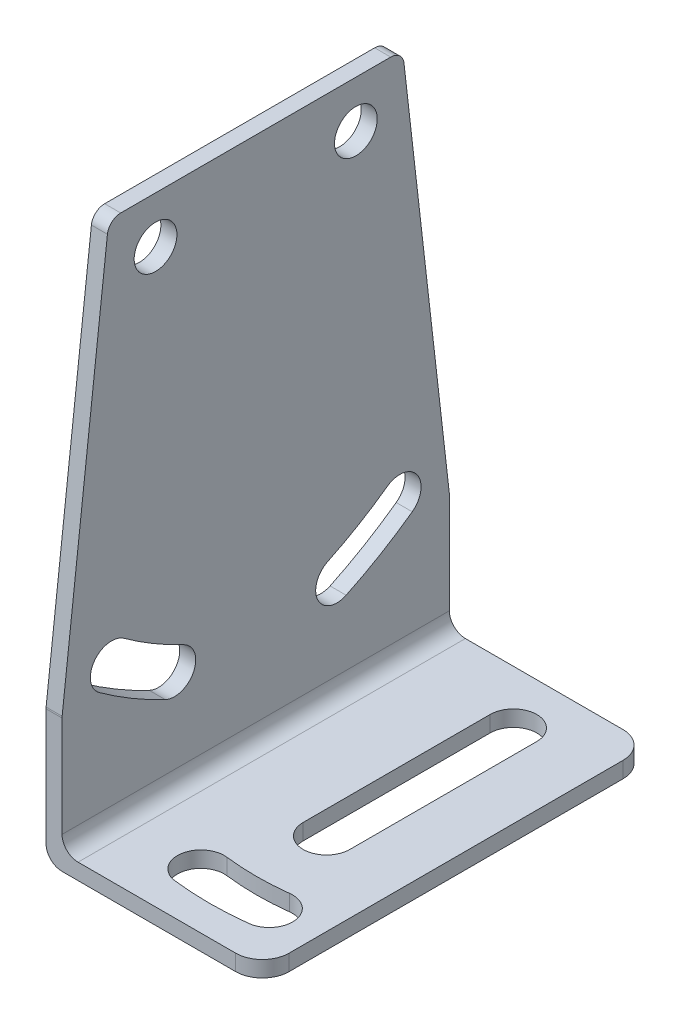
SolidWorks part; units mm, degrees
material "Cast Stainless Steel"
ref_plane "Front Plane" through (0, 0, 0) normal (0, 0, 1) x (1, 0, 0)
ref_plane "Top Plane" through (0, 0, 0) normal (0, 1, 0) x (1, 0, 0)
ref_plane "Right Plane" through (0, 0, 0) normal (1, 0, 0) x (0, 0, -1)
sketch "Sketch1" plane through (0, 0, 0) normal (1, 0, 0) x (0, 0, -1)
  line L0 (0, 0) -> (0, -40.5) construction
  line L1 (-7.5, 0) -> (7.5, 0)
  line L2 (-7.5, -3.5) -> (8.5, -30.5) construction
  line L3 (-7.5, -3.5) -> (10.7896, -28.9989) construction
  line L4 (-7.5, -3.5) -> (6.0839, -31.7875) construction
  line L5 (-14.5, -40.5) -> (14.5, -40.5)
  line L6 (7.5, 0) -> (10.1082, 0)
  line L7 (11.1017, -0.886) -> (14.4935, -30.4432)
  line L8 (14.5, -30.5572) -> (14.5, -40.5)
  line L9 (-7.5, 0) -> (-10.1082, 0)
  line L10 (-11.1017, -0.886) -> (-14.4935, -30.4421)
  line L11 (-14.5, -30.5561) -> (-14.5, -40.5)
  circle A0 centre (-7.5, -3.5) radius 1.6
  arc A2 (9.857, -27.6988) -> (9.736, -27.7948) centre (10.7896, -28.9989) ccw
  arc A3 (5.5335, -30.2851) -> (5.3913, -30.3452) centre (6.0839, -31.7875) ccw
  arc A4 (10.7896, -28.9989) -> (6.0839, -31.7875) centre (-7.0515, -4.2569) cw construction
  arc A5 (6.7696, -33.2248) -> (11.721, -30.2907) centre (-7.0515, -4.2569) ccw
  arc A6 (5.3981, -30.3502) -> (9.8581, -27.7072) centre (-7.0515, -4.2569) ccw
  arc A7 (5.3981, -30.3502) -> (6.7696, -33.2248) centre (6.0839, -31.7875) ccw
  arc A8 (11.721, -30.2907) -> (9.8581, -27.7072) centre (10.7896, -28.9989) ccw
  arc A9 (-10.7896, -28.9989) -> (-6.0839, -31.7875) centre (7.0515, -4.2569) ccw construction
  arc A10 (-6.7696, -33.2248) -> (-11.721, -30.2907) centre (7.0515, -4.2569) cw
  arc A11 (-5.3981, -30.3502) -> (-9.8581, -27.7072) centre (7.0515, -4.2569) cw
  arc A12 (-5.3981, -30.3502) -> (-6.7696, -33.2248) centre (-6.0839, -31.7875) cw
  arc A13 (-11.721, -30.2907) -> (-9.8581, -27.7072) centre (-10.7896, -28.9989) cw
  circle A14 centre (7.5, -3.5) radius 1.6
  arc A15 (-14.4935, -30.4421) -> (-14.5, -30.5561) centre (-13.5, -30.5561) ccw
  arc A16 (14.4935, -30.4432) -> (14.5, -30.5572) centre (13.5, -30.5572) cw
  arc A17 (10.1082, 0) -> (11.1017, -0.886) centre (10.1082, -1) cw
  arc A18 (-10.1082, 0) -> (-11.1017, -0.886) centre (-10.1082, -1) ccw
  point P15 (8.4994, -30.4989)
  point P23 (7.5, -3.5)
  point P24 (-8.4994, -30.4989)
  point P39 (-14.5, -30.4989)
  point P42 (14.5, -30.5)
  point P45 (11, 0)
  point P48 (-11, 0)
  dimension "D3" = 27
  dimension "D16" = 3.2
  dimension "D17" = 3.2
  dimension "D18" = 3.5
  dimension "D21" = 1
  dimension "D1" = 15
  dimension "D2" = 7.5
  dimension "D4" = 29
  dimension "D5" = 3.5
  dimension "D6" = 7.5
  dimension "D7" = 14.5
  dimension "D8" = 40.5
  dimension "D9" = 16
  dimension "D10" = 3.5
  dimension "D11" = 31.3847
  dimension "D12" = 31.38
  dimension "D13" = 31.38
  dimension "D14" = 10
  dimension "D15" = 5
  dimension "D19" = 10
  dimension "D20" = 10.0011
extrude "Boss-Extrude1" add sketch "Sketch1" along normal blind 1.2 contours A15 L10 A18 L9 L1 L6 A17 L7 A16 L8 L5 L11 | A6 A8 A5 A7 | A10 A13 A11 A12 | A0 | A14
sketch "Sketch2" plane through (1.2, 0, 0) normal (1, 0, 0) x (0, 0, -1)
  line L1 (-14.5, -40.5) -> (14.5, -40.5)
  line L2 (-14.5, -40.5) -> (-14.5, -39.3)
  line L3 (-14.5, -39.3) -> (14.5, -39.3)
  line L4 (14.5, -40.5) -> (14.5, -39.3)
  line L5 (14.5, -30.5572) -> (14.5, -40.5) construction
  dimension "D1" = 1.2
  dimension "D2" = 29
extrude "Boss-Extrude2" add sketch "Sketch2" along normal blind 15
sketch "Sketch3" plane through (0, -39.3, 0) normal (0, 1, 0) x (1, 0, 0)
  line L0 (10, 17.234) -> (10, -18.6155) construction
  line L1 (0, 11.1017) -> (0, 14.4935) construction
  line L2 (0, 0) -> (21.3569, 0) construction
  line L3 (10, -3.5) -> (10, 10.5) construction
  line L4 (8.25, -3.5) -> (8.25, 10.5)
  line L5 (11.75, -3.5) -> (11.75, 10.5)
  line L6 (10, 10.5) -> (6.495, -18.0457) construction
  line L7 (10, 10.5) -> (13.5324, -18.2695) construction
  arc A0 (8.25, -3.5) -> (11.75, -3.5) centre (10, -3.5) ccw
  arc A1 (11.75, 10.5) -> (8.25, 10.5) centre (10, 10.5) ccw
  arc A2 (12.5593, -10.3435) -> (7.4407, -10.3435) centre (10, 10.8738) cw construction
  arc A7 (7.2312, -12.0809) -> (12.7688, -12.0809) centre (10, 10.8738) ccw
  arc A8 (7.6503, -8.6061) -> (12.3497, -8.6061) centre (10, 10.8738) ccw
  arc A9 (7.6503, -8.6061) -> (7.2312, -12.0809) centre (7.4407, -10.3435) ccw
  arc A10 (12.7688, -12.0809) -> (12.3497, -8.6061) centre (12.5593, -10.3435) ccw
  point P9 (10, 3.5)
  point P16 (10, -10.5)
  point P18 (12.5593, -10.3435)
  point P19 (7.4407, -10.3435)
  point P23 (10, -10.4973)
  dimension "D2" = 10.5
  dimension "D7" = 21
  dimension "D1" = 10
  dimension "D3" = 3.5
  dimension "D4" = 14
  dimension "D5" = 14
  dimension "D6" = 7
  dimension "D8" = 21
  dimension "D9" = 21
extrude "Cut-Extrude1" cut sketch "Sketch3" against normal through all
fillet "Fillet1" radius 1.2 1 edges at (1.2, -39.3, 0)
fillet "Fillet2" radius 1.2 1 edges at (0, -40.5, 0)
fillet "Fillet3" radius 2 2 edges at (16.2, -39.9, 14.5) (16.2, -39.9, -14.5)
